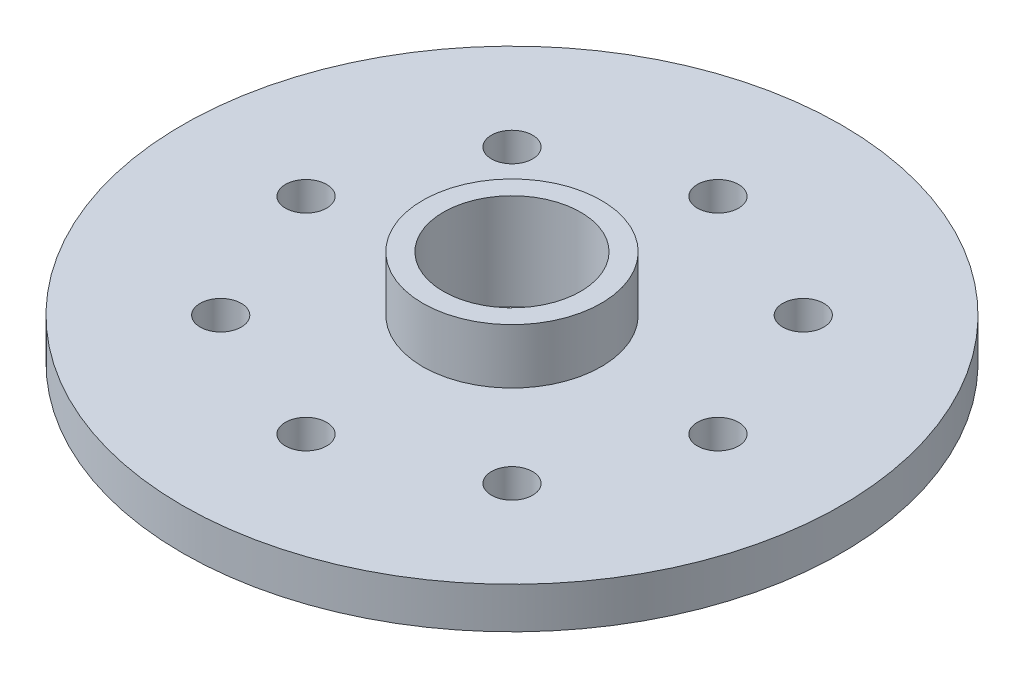
SolidWorks part; units mm, degrees
material "BUTYL"
ref_plane "Front Plane" through (0, 0, 0) normal (0, 0, 1) x (1, 0, 0)
ref_plane "Top Plane" through (0, 0, 0) normal (0, 1, 0) x (1, 0, 0)
ref_plane "Right Plane" through (0, 0, 0) normal (1, 0, 0) x (0, 0, -1)
sketch "Sketch1" plane through (0, 0, 0) normal (0, 1, 0) x (1, 0, 0)
  circle A0 centre (0, 0) radius 12
  dimension "D1" = 24
extrude "Boss-Extrude1" add sketch "Sketch1" along normal blind 1.5
sketch "Sketch2" plane through (0, 1.5, 0) normal (0, 1, 0) x (1, 0, 0)
  circle A0 centre (0, 0) radius 3.25
  dimension "D1" = 6.5
extrude "Boss-Extrude2" add sketch "Sketch2" along normal blind 2
sketch "Sketch3" plane through (0, 3.5, 0) normal (0, 1, 0) x (1, 0, 0)
  circle A0 centre (0, 0) radius 2.5
  dimension "D1" = 5
extrude "Cut-Extrude1" cut sketch "Sketch3" against normal through all
sketch "Sketch4" plane through (0, 1.5, 0) normal (0, 1, 0) x (1, 0, 0)
  line L0 (-12, 0) -> (12, 0) construction
  circle A0 centre (0, 0) radius 12 construction
  circle A1 centre (-7.5, 0) radius 0.7653
  circle A2 centre (7.5, 0) radius 0.7653
  dimension "D3" = 1.5306
  dimension "D1" = 15
  dimension "D2" = 7.5
extrude "Cut-Extrude2" [suppressed] cut sketch "Sketch4" against normal blind 2
sketch "Sketch5" plane through (0, 1.5, 0) normal (0, 1, 0) x (1, 0, 0)
  circle A0 centre (0, 0) radius 7.5 construction
  circle A1 centre (0, 7.5) radius 0.75
  circle A2 centre (5.3033, 5.3033) radius 0.75
  circle A3 centre (7.5, 0) radius 0.75
  circle A4 centre (5.3033, -5.3033) radius 0.75
  circle A5 centre (0, -7.5) radius 0.75
  circle A6 centre (-5.3033, -5.3033) radius 0.75
  circle A7 centre (-7.5, 0) radius 0.75
  circle A8 centre (-5.3033, 5.3033) radius 0.75
  point P21 (0, 0)
  dimension "D1" = 15
  dimension "D3" = 1.5
  dimension "D2" = 8
extrude "Cut-Extrude3" cut sketch "Sketch5" against normal blind 2
